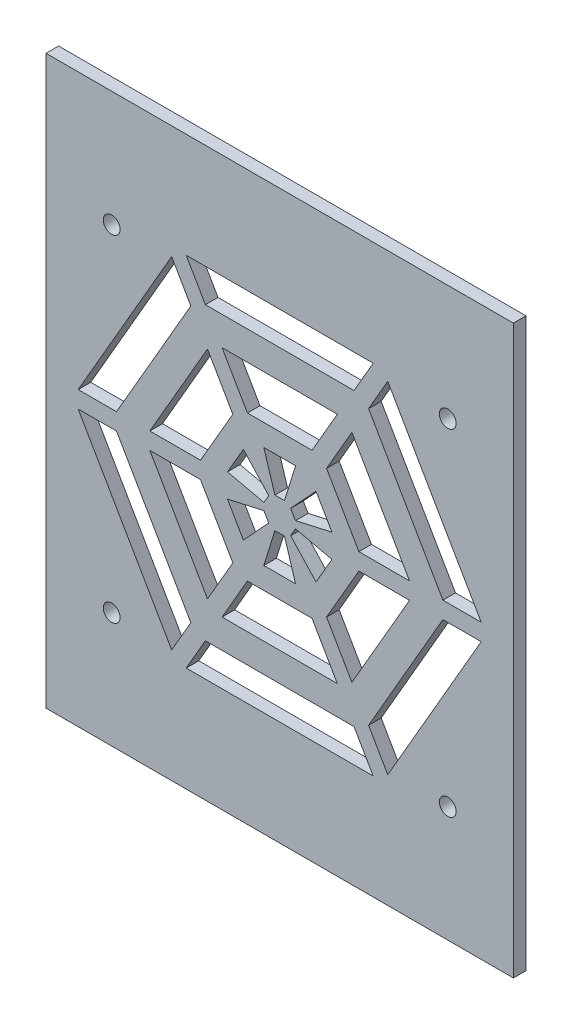
SolidWorks part; units mm, degrees
ref_plane "Front Plane" through (0, 0, 0) normal (0, 0, 1) x (1, 0, 0)
ref_plane "Top Plane" through (0, 0, 0) normal (0, 1, 0) x (1, 0, 0)
ref_plane "Right Plane" through (0, 0, 0) normal (1, 0, 0) x (0, 0, -1)
sketch "Sketch1" plane through (0, 0, 0) normal (0, 0, 1) x (1, 0, 0)
  line L0 (-3, -58.7702) -> (0, -58.7702) construction
  line L1 (-111.25, 76.2298) -> (0, 76.2298)
  line L2 (-111.25, 76.2298) -> (-111.25, -58.7702)
  line L3 (-111.25, -58.7702) -> (0, -58.7702)
  line L4 (0, 76.2298) -> (0, -58.7702)
extrude "Boss-Extrude1" add sketch "Sketch1" along normal blind 3 contours L1 L4 L3 L2
sketch "Sketch2" plane through (0, 0, 3) normal (0, 0, 1) x (1, 0, 0)
  line L0 (-37.9344, -25.9113) -> (-33.3712, -33.815)
  line L1 (0, -58.7702) -> (-111.25, -58.7702)
  line L2 (-69.346, -19.0357) -> (-63.3156, -8.5907)
  line L3 (-94.4703, 6.7298) -> (-103.5968, 6.7298)
  line L4 (-86.5311, 10.7298) -> (-74.4703, 10.7298)
  line L5 (-72.8101, 34.4952) -> (-66.7797, 24.0503)
  line L6 (-73.3156, 43.3708) -> (-77.8788, 51.2745)
  line L7 (-37.9344, 43.3708) -> (-33.3712, 51.2745)
  line L8 (-33.3712, 51.2745) -> (-77.8788, 51.2745)
  line L9 (-81.3429, 49.2745) -> (-103.5968, 10.7298)
  line L10 (-103.5968, 6.7298) -> (-81.3429, -31.815)
  line L11 (-77.8788, -33.815) -> (-33.3712, -33.815)
  line L12 (-29.9071, -31.815) -> (-7.6532, 6.7298)
  line L13 (-7.6532, 10.7298) -> (-29.9071, 49.2745)
  line L14 (-34.4703, 41.3708) -> (-29.9071, 49.2745)
  line L15 (-37.9344, 43.3708) -> (-73.3156, 43.3708)
  line L16 (-76.7797, 41.3708) -> (-94.4703, 10.7298)
  line L17 (-94.4703, 6.7298) -> (-76.7797, -23.9113)
  line L18 (-73.3156, -25.9113) -> (-37.9344, -25.9113)
  line L19 (-34.4703, -23.9113) -> (-16.7797, 6.7298)
  line L20 (-16.7797, 10.7298) -> (-34.4703, 41.3708)
  line L21 (-41.904, 36.4952) -> (-69.346, 36.4952)
  line L22 (-72.8101, 34.4952) -> (-86.5311, 10.7298)
  line L23 (-86.5311, 6.7298) -> (-72.8101, -17.0357)
  line L24 (-69.346, -19.0357) -> (-41.904, -19.0357)
  line L25 (-38.4399, -17.0357) -> (-24.7189, 6.7298)
  line L26 (-24.7189, 10.7298) -> (-38.4399, 34.4952)
  line L27 (-47.9344, 26.0503) -> (-63.3156, 26.0503)
  line L28 (-66.7797, 24.0503) -> (-74.4703, 10.7298)
  line L29 (-74.4703, 6.7298) -> (-66.7797, -6.5907)
  line L30 (-63.3156, -8.5907) -> (-47.9344, -8.5907)
  line L31 (-44.4703, -6.5907) -> (-36.7797, 6.7298)
  line L32 (-36.7797, 10.7298) -> (-44.4703, 24.0503)
  line L33 (-51.8438, 20.9004) -> (-59.4062, 20.9004)
  line L34 (-64.2745, 18.0897) -> (-68.0557, 11.5405)
  line L35 (-68.0557, 5.9191) -> (-64.2745, -0.6302)
  line L36 (-59.4062, -3.4409) -> (-51.8438, -3.4409)
  line L37 (-46.9755, -0.6302) -> (-43.1943, 5.9191)
  line L38 (-43.1943, 11.5405) -> (-46.9755, 18.0897)
  line L39 (-16.7797, 10.7298) -> (-7.6532, 10.7298)
  line L40 (-24.7189, 6.7298) -> (-36.7797, 6.7298)
  line L41 (-29.9071, -31.815) -> (-34.4703, -23.9113)
  line L42 (-38.4399, -17.0357) -> (-44.4703, -6.5907)
  line L43 (-68.0557, 11.5405) -> (-59.2113, 9.5407)
  line L44 (-46.9755, -0.6302) -> (-53.1296, 6.0294)
  line L45 (-81.3429, 49.2745) -> (-76.7797, 41.3708)
  line L46 (-59.4062, 20.9004) -> (-56.7159, 12.241)
  line L47 (-54.5341, 12.241) -> (-51.8438, 20.9004)
  line L48 (-53.1296, 11.4301) -> (-46.9755, 18.0897)
  line L49 (-77.8788, -33.815) -> (-73.3156, -25.9113)
  line L50 (-43.1943, 11.5405) -> (-52.0387, 9.5407)
  line L51 (-51.8438, -3.4409) -> (-54.5341, 5.2185)
  line L52 (-59.4062, -3.4409) -> (-56.7159, 5.2185)
  line L53 (-81.3429, -31.815) -> (-76.7797, -23.9113)
  line L54 (-64.2745, -0.6302) -> (-58.1204, 6.0294)
  line L55 (-68.0557, 5.9191) -> (-59.2113, 7.9189)
  line L56 (-72.8101, -17.0357) -> (-66.7797, -6.5907)
  line L57 (-103.5968, 10.7298) -> (-94.4703, 10.7298)
  line L58 (-52.0387, 7.9189) -> (-43.1943, 5.9191)
  line L59 (-54.4827, 12.4066) -> (-56.7673, 12.4066)
  line L60 (-58.2381, 11.5575) -> (-59.3804, 9.5789)
  line L61 (-7.6532, 6.7298) -> (-16.7797, 6.7298)
  line L62 (-59.3804, 7.8806) -> (-58.2381, 5.9021)
  line L63 (-56.7673, 5.0529) -> (-54.4827, 5.0529)
  line L64 (-53.0119, 5.9021) -> (-51.8696, 7.8806)
  line L65 (-51.8696, 9.5789) -> (-53.0119, 11.5575)
  line L66 (-58.1204, 11.4301) -> (-64.2745, 18.0897)
  line L67 (-74.4703, 6.7298) -> (-86.5311, 6.7298)
  line L76 (-63.3156, 26.0503) -> (-69.346, 36.4952)
  line L77 (-47.9344, 26.0503) -> (-41.904, 36.4952)
  line L82 (-44.4703, 24.0503) -> (-38.4399, 34.4952)
  line L83 (-36.7797, 10.7298) -> (-24.7189, 10.7298)
  line L92 (-47.9344, -8.5907) -> (-41.904, -19.0357)
  circle A1 centre (-15.625, 48.7298) radius 2
  circle A2 centre (-95.625, 48.7298) radius 2
  circle A3 centre (-95.625, -31.2702) radius 2
  circle A4 centre (-15.625, -31.2702) radius 2
  dimension "D1" = 4
  dimension "D2" = 4
  dimension "D3" = 4
  dimension "D4" = 4
extrude "Cut-Extrude2" cut sketch "Sketch2" against normal blind 10 contours L9 L57 L16 L45 | L15 L7 L8 L6 | L20 L39 L13 L14 | L12 L61 L19 L41 | L49 L11 L0 L18 | L10 L53 L17 L3 | L28 L5 L22 L4 | L29 L67 L23 L56 | L92 L30 L2 L24 | L42 L25 L40 L31 | L32 L83 L26 L82 | L27 L77 L21 L76 | L59 L47 L33 L46 | L60 L66 L34 L43 | L62 L55 L35 L54 | L63 L52 L36 L51 | L64 L44 L37 L58 | L65 L50 L38 L48 | A4 | A3 | A2 | A1
